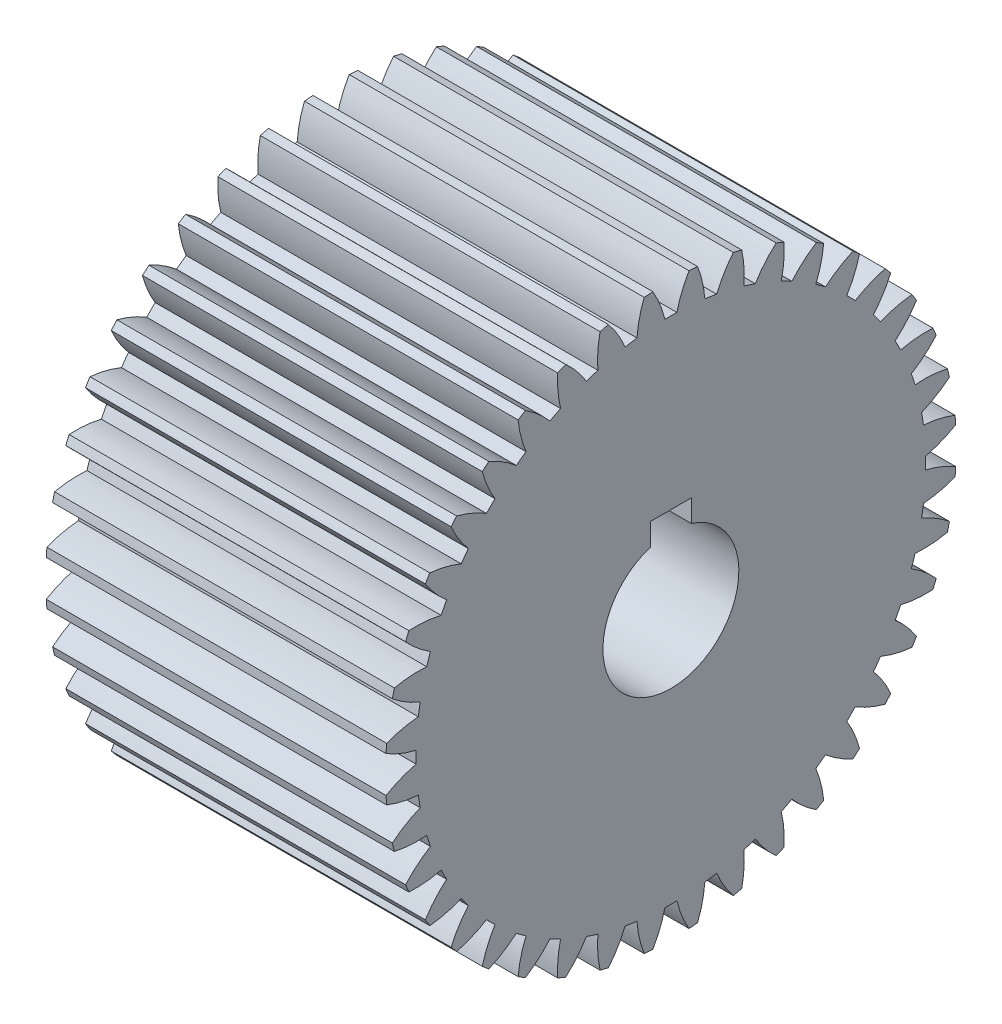
SolidWorks part; units mm, degrees
ref_plane "Plane1" through (0, 0, 0) normal (0, 0, 1) x (1, 0, 0)
ref_plane "Plane2" through (0, 0, 0) normal (0, 1, 0) x (1, 0, 0)
ref_plane "Plane3" through (0, 0, 0) normal (1, 0, 0) x (0, 0, -1)
sketch "HoldingSke" plane through (0, 0, 0) normal (0, 1, 0) x (1, 0, 0)
  line L0 (0, 0) -> (0.383, -0.3214)
  line L1 (-15, 0) -> (100, 0) construction
  line L2 (0, 0) -> (-2.1039, 2.3779)
  line L3 (0, 0) -> (-11.863, 4.5341)
  line L4 (0, 0) -> (6.6156, 5.5511)
  line L5 (0, 0) -> (-46.8476, -17.4728)
  line L6 (0, 0) -> (-41.4481, -27.9652)
  line L7 (-2.1039, 2.3779) -> (8.6586, 51.2059)
  line L8 (-76.2, 54.61) -> (-73.4, 54.61)
  line L9 (-71.009, 38.7566) -> (-53.1078, 45.2721)
  line L10 (-76.2, 71.12) -> (104.1128, 71.12)
  line L11 (0, 0) -> (-50, 0)
  line L12 (-76.2, 101.6) -> (-76.133, 101.6)
  line L13 (24.9733, 27.94) -> (52.9518, 28.4284)
  line L14 (24.9733, 27.94) -> (24.9743, 27.94)
  line L15 (24.9733, 27.94) -> (100.4006, 29.5858)
  line L16 (-63.627, -2) -> (-12.827, -2)
  circle A0 centre (0, 0) radius 10
  circle A1 centre (0, 0) radius 37.499
  circle A2 centre (0, 0) radius 37.5
  circle A3 centre (0, 0) radius 10
  dimension "MHD" = 74.998
  dimension "Hub_dia" = 75
  dimension "Bore" = 20
  dimension "MBD" = 20
  dimension "Num_teeth" = 40
  dimension "Pitch" = 0.5
  dimension "Overall_len" = 50
  dimension "Show_teeth" = 40
  dimension "Thickness" = 50
  dimension "OAL" = 50.0001
  dimension "T_dim" = 2.8
  dimension "Ap" = 20
  dimension "H" = 19.05
  dimension "Pitch_radius" = 180.3128
  dimension "Width" = 50
  dimension "Backlash" = 0.067
  dimension "Addendum_fac" = 1
  dimension "Dedendum_fac" = 1.25
  dimension "Clearance_fac" = 0.25
  dimension "Dedendum_add" = 0.001
  dimension "Module" = 2
sketch "BasProSke" plane through (0, 0, 0) normal (0, 1, 0) x (1, 0, 0)
  line L0 (-10, 0) -> (60, 0) construction
  line L1 (0, 0) -> (0, 42)
  line L2 (0, 0) -> (50, 0)
  line L3 (50, 0) -> (50, 42)
  line L4 (50, 42) -> (0, 42)
  dimension "Thickness" = 50
  dimension "Diameter" = 84
revolve "Base-Revolve" add sketch "BasProSke" angle 360 about L0
sketch "TooCutSke" plane through (0, 0, 0) normal (1, 0, 0) x (0, 0, -1)
  line L1 (0, 0) -> (0, 107) construction
  line L2 (0, 0) -> (-1.6876, 39.9644) construction
  line L3 (0, 0) -> (-6.2726, 79.7007) construction
  line L4 (-1.6876, 39.9644) -> (-3.1363, 39.8504) construction
  arc A0 (0.8828, 37.4886) -> (-0.8828, 37.4886) centre (0, 0) ccw
  arc A1 (2.6784, 41.94) -> (-2.6784, 41.94) centre (0, 0) ccw
  circle A2 centre (0, 0) radius 40 construction
  circle A3 centre (0, 0) radius 37.5877 construction
  arc A4 (-0.8828, 37.4886) -> (-2.6784, 41.94) centre (-16.451, 33.7965) ccw
  arc A5 (2.6784, 41.94) -> (0.8828, 37.4886) centre (16.451, 33.7965) ccw
  dimension "Root_dia" = 74.998
  dimension "Overcut_dia" = 84.0508
  dimension "Pitch_dia" = 80
  dimension "Base_dia" = 75.1754
  dimension "Flank_rad" = 16
  dimension "Half_ang" = 4.5
  dimension "Half_CT" = 1.4531
extrude "ToothCut" cut sketch "TooCutSke" along normal through all
fillet "Breaks" [suppressed] radius 0.04
fillet "RootFillets" [suppressed] radius 0.501
pattern_circular "TeethCuts" count 40 every 9 about axis through (-10, 0, 0) along (1, 0, 0) of "ToothCut", "RootFillets", "Breaks"
sketch "HubNeaOneSke" plane through (0, 0, 0) normal (-1, 0, 0) x (0, 0, 1)
  circle A0 centre (0, 0) radius 37.499
  dimension "Diameter" = 74.998
extrude "HubNearOne" [suppressed] add sketch "HubNeaOneSke" along normal blind 34.0001
sketch "HubNeaBotSke" plane through (0, 0, 0) normal (-1, 0, 0) x (0, 0, 1)
  circle A0 centre (0, 0) radius 37.499
  dimension "Diameter" = 74.998
extrude "HubNearBoth" [suppressed] add sketch "HubNeaBotSke" along normal blind 17
ref_plane "FarPln" through (50, 0, 0) normal (1, 0, 0) x (0, 0, -1)
sketch "HubFarSke" plane through (50, 0, 0) normal (1, 0, 0) x (0, 0, -1)
  circle A0 centre (0, 0) radius 37.499
  dimension "Diameter" = 74.998
extrude "HubFar" [suppressed] add sketch "HubFarSke" along normal blind 17
sketch "BorSke" plane through (0, 0, 0) normal (1, 0, 0) x (0, 0, -1)
  circle A0 centre (0, 0) radius 10
  dimension "Diameter" = 20
extrude "Bore" cut sketch "BorSke" along normal mid plane 100.0001
sketch "KeySke" plane through (0, 0, 0) normal (1, 0, 0) x (0, 0, -1)
  line L0 (-3, 0) -> (-3, 12.8)
  line L1 (-3, 12.8) -> (3, 12.8)
  line L2 (3, 12.8) -> (3, 0)
  line L3 (0, 0) -> (0, 34) construction
  line L4 (-3, 0) -> (3, 0)
  dimension "Offset" = 12.8
  dimension "Width" = 6
extrude "Keyway" cut sketch "KeySke" along normal mid plane 100.0001
pattern_circular "Keyway2" [suppressed] count 2 every 90 about axis through (-10, 0, 0) along (1, 0, 0)
equation "' \"Module@HoldingSke\" = 6.35"
equation "' \"Num_teeth@HoldingSke\" = 12"
equation "' \"Ap@HoldingSke\" =  20"
equation "' \"Ap@HoldingSke\" = 20"
equation "' \"Width@HoldingSke\" = 0.5 * 25.4"
equation "' \"Hub_dia@HoldingSke\"= 1 * 25.4"
equation "' \"Hub_dia@HoldingSke\" = 1 * 25.4"
equation "' \"Overall_len@HoldingSke\" = 1.0 * 25.4"
equation "' \"Bore@HoldingSke\" = 0.75 * 25.4"
equation "' \"T_dim@HoldingSke\" = 0.1 * 25.4"
equation "' \"Width@KeySke\" = 0.25 * 25.4"
equation "' \"Show_teeth@HoldingSke\" = 13"
equation "' \"Backlash@HoldingSke\" = 0.009 * 25.4"
equation "' \"Addendum_fac@HoldingSke\" = 1.0"
equation "' \"Dedendum_fac@HoldingSke\" = 1.25"
equation "' \"Dedendum_add@HoldingSke\" = 0.00005 * 25.4"
equation "' \"Clearance_fac@HoldingSke\" = 0.25"
equation "\"Pitch@HoldingSke\" = 1 / \"Module@HoldingSke\""
equation "\"Overcut_dia@TooCutSke\" = (\"Num_teeth@HoldingSke\" + 2 * \"Addendum_fac@HoldingSke\") / \"Pitch@HoldingSke\" + 0.002 * 25.4"
equation "\"Pitch_dia@TooCutSke\" = \"Num_teeth@HoldingSke\" / \"Pitch@HoldingSke\""
equation "\"Base_dia@TooCutSke\" = \"Num_teeth@HoldingSke\" / \"Pitch@HoldingSke\" * cos((\"Ap@HoldingSke\"  * 3.14159265 / 180))"
equation "\"Root_dia@TooCutSke\" = (\"Num_teeth@HoldingSke\" + 2) / \"Pitch@HoldingSke\" - 2 * (\"Addendum_fac@HoldingSke\" + \"Dedendum_fac@HoldingSke\") / \"Pitch@HoldingSke\" - \"Dedendum_add@HoldingSke\" * 2"
equation "\"Half_ang@TooCutSke\" = 180 / \"Num_teeth@HoldingSke\""
equation "\"Half_CT@TooCutSke\" = \"Num_teeth@HoldingSke\" / \"Pitch@HoldingSke\" * sin((3.14159265 / 2 / \"Num_teeth@HoldingSke\")) / 2 - 7 * \"Backlash@HoldingSke\" / 4"
equation "\"Flank_rad@TooCutSke\" = \"Num_teeth@HoldingSke\" / \"Pitch@HoldingSke\" / 5"
equation "\"Radius@RootFillets\" = \"Clearance_fac@HoldingSke\" / \"Pitch@HoldingSke\" + \"Dedendum_add@HoldingSke\""
equation "\"Break_rad@Breaks\" = 0.02 / \"Pitch@HoldingSke\""
equation "\"Thickness@HoldingSke\" = \"Width@HoldingSke\""
equation "\"OAL@HoldingSke\" = \"Thickness@HoldingSke\""
equation "\"MHD@HoldingSke\" = (\"Num_teeth@HoldingSke\" + 2) / \"Pitch@HoldingSke\" - 2 * (\"Addendum_fac@HoldingSke\" + \"Dedendum_fac@HoldingSke\")  / \"Pitch@HoldingSke\" - \"Dedendum_add@HoldingSke\" * 2"
equation "\"MBD@HoldingSke\" = (\"Num_teeth@HoldingSke\" + 2) / \"Pitch@HoldingSke\" - 2 * (\"Addendum_fac@HoldingSke\" + \"Dedendum_fac@HoldingSke\")  / \"Pitch@HoldingSke\" - \"Dedendum_add@HoldingSke\" * 2 - 0.002 * 25.4"
equation "\"MHD@HoldingSke\" = ((sgn( \"MHD@HoldingSke\" - \"Hub_dia@HoldingSke\" )-1)*( \"MHD@HoldingSke\" - \"Hub_dia@HoldingSke\" ))/-2+ \"Hub_dia@HoldingSke\""
equation "\"MBD@HoldingSke\" = ((sgn( \"MBD@HoldingSke\" - \"Bore@HoldingSke\" )-1)*( \"MBD@HoldingSke\" - \"Bore@HoldingSke\" ))/-2+ \"Bore@HoldingSke\""
equation "\"OAL@HoldingSke\" = ((sgn( \"OAL@HoldingSke\" - \"Overall_len@HoldingSke\" )+1)*( \"OAL@HoldingSke\" - \"Overall_len@HoldingSke\" ))/2 + \"Overall_len@HoldingSke\" + 0.000002 * 25.4"
equation "\"Num_teeth@TeethCuts\" = int( \"Show_teeth@HoldingSke\" ) + 1"
equation "\"Num_teeth@TeethCuts\" = ((sgn( \"Num_teeth@TeethCuts\" - \"Num_teeth@HoldingSke\" )-1)*( \"Num_teeth@TeethCuts\" - \"Num_teeth@HoldingSke\" ))/-2+ \"Num_teeth@HoldingSke\""
equation "\"Num_teeth@TeethCuts\" = ((sgn( \"Num_teeth@TeethCuts\" - 2.0)+1)*( \"Num_teeth@TeethCuts\" - 2.0))/2 +2.0"
equation "\"Angle@TeethCuts\" = 360.0 / \"Num_teeth@HoldingSke\""
equation "\"Diameter@BasProSke\" = (\"Num_teeth@HoldingSke\" + 2 * \"Addendum_fac@HoldingSke\") / \"Pitch@HoldingSke\""
equation "\"Thickness@BasProSke\"  = \"Thickness@HoldingSke\""
equation "' \"Fillet_rad@BasProSke\" =  \"Thickness@HoldingSke\" * 0.05"
equation "' \"Fillet_rad@BasProSke\" = \"Thickness@HoldingSke\" * 0.05"
equation "\"MHD@HoldingSke\" = ((sgn( \"MHD@HoldingSke\" - \"Root_dia@TooCutSke\" )-1)*( \"MHD@HoldingSke\" - \"Root_dia@TooCutSke\" ))/-2+ \"Root_dia@TooCutSke\""
equation "\"Diameter@HubNeaOneSke\" = \"MHD@HoldingSke\""
equation "\"Length@HubNearOne\" = \"OAL@HoldingSke\" - \"Thickness@BasProSke\""
equation "\"Diameter@HubNeaBotSke\" = \"MHD@HoldingSke\""
equation "\"Length@HubNearBoth\" = ( \"OAL@HoldingSke\" - \"Thickness@BasProSke\" ) / 2.0"
equation "\"Thickness@FarPln\" = \"Thickness@BasProSke\""
equation "\"Diameter@HubFarSke\" = \"MHD@HoldingSke\""
equation "\"Length@HubFar\" = ( \"OAL@HoldingSke\" - \"Thickness@BasProSke\" ) / 2.0"
equation "\"Diameter@BorSke\" = \"MBD@HoldingSke\""
equation "\"D1@Bore\" = \"OAL@HoldingSke\" * 2.0"
equation "\"D1@Keyway\" = \"OAL@HoldingSke\" * 2.0"
equation "\"Offset@KeySke\" = \"T_dim@HoldingSke\" + \"MBD@HoldingSke\" / 2.0"
